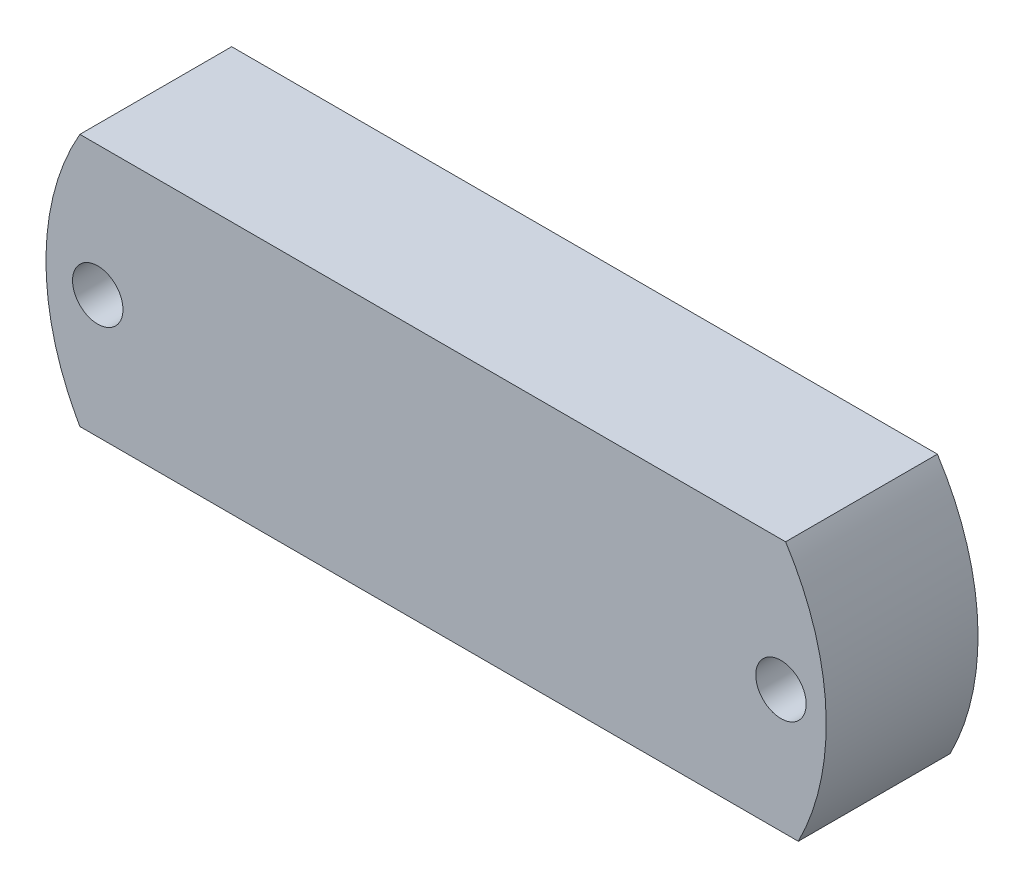
SolidWorks part; units mm, degrees
material "ABS PC"
ref_plane "Front Plane" through (0, 0, 0) normal (0, 0, 1) x (1, 0, 0)
ref_plane "Top Plane" through (0, 0, 0) normal (0, 1, 0) x (1, 0, 0)
ref_plane "Right Plane" through (0, 0, 0) normal (1, 0, 0) x (0, 0, -1)
sketch "Sketch1" plane through (0, 0, 0) normal (0, 0, 1) x (1, 0, 0)
  circle A0 centre (0, 0) radius 66.4845
  dimension "D1" = 132.969
extrude "Boss-Extrude1" add sketch "Sketch1" along normal blind 11.43
sketch "Sketch2" plane through (0, 0, 0) normal (0, 0, -1) x (-1, 0, 0)
  line L0 (0, 66.4845) -> (85.1652, 66.4845) construction
  circle A0 centre (0, 0) radius 66.4845 construction
ref_plane "Plane1" through (0, 10.9988, -24.7038) normal (0, -0.4067, 0.9135) x (1, 0, 0)
sketch "Sketch3" plane through (0, 10.9988, -24.7038) normal (0, -0.4067, 0.9135) x (1, 0, 0)
  line L1 (27.5387, 25.5449) -> (-13.7363, 25.5449)
  line L2 (27.5387, 25.5449) -> (27.5387, 49.8019)
  line L3 (27.5387, 49.8019) -> (-13.7363, 49.8019)
  line L4 (-13.7363, 25.5449) -> (-13.7363, 49.8019)
  line L5 (27.5387, 25.5449) -> (-13.7363, 49.8019) construction
  line L6 (27.5387, 49.8019) -> (-13.7363, 25.5449) construction
  line L7 (0, 60.7366) -> (-85.1652, 60.7366) construction
  point P0 (6.9012, 37.6734)
  dimension "D1" = 41.275
  dimension "D2" = 13.7363
  dimension "D3" = 35.1917
  dimension "D4" = 24.257
extrude "Cut-Extrude1" cut sketch "Sketch3" against normal blind 33.02 and the other way blind 13.2589
sketch "Sketch4" plane through (0, 0, 0) normal (0, 0, -1) x (-1, 0, 0)
  circle A0 centre (0, 0) radius 30.1625
  dimension "D1" = 60.325
extrude "Cut-Extrude2" cut sketch "Sketch4" against normal through all
sketch "Sketch6" plane through (0, 0, 0) normal (0, 0, -1) x (-1, 0, 0)
  line L0 (-32.6187, 45.625) -> (18.8163, 45.625) construction
  line L1 (-27.5387, 33.8863) -> (-27.5387, 51.1023) construction
  line L2 (13.7363, 33.8863) -> (13.7363, 54.515) construction
  line L3 (13.7363, 54.515) -> (-27.5387, 54.515) construction
  dimension "D1" = 5.08
  dimension "D2" = 5.08
  dimension "D3" = 8.89
hole_wizard "#6 Clearance Hole1" positions "Sketch8" profile "Sketch7" hole size "#6" standard "ANSI Inch" end condition through all
sketch "Sketch8" plane through (0, 0, 0) normal (0, 0, -1) x (-1, 0, 0)
  point P0 (-32.6187, 45.625)
  point P3 (18.8163, 45.625)
sketch "Sketch7" plane through (32.6187, 45.625, 0) normal (1, 0, 0) x (0, 1, 0)
  line L0 (0, 0) -> (0, 11.43)
  line L1 (0, 11.43) -> (1.8986, 11.43)
  line L2 (1.8986, 11.43) -> (1.8986, 0)
  line L5 (1.8986, 0) -> (0, 0)
  line L11 (0, -6.35) -> (0, 107.95) construction
  dimension "Thru Hole Dia." = 3.7973
  dimension "Thru Hole Depth" = 11.43
pattern_circular "CirPattern1" count 5 over 360 about axis through (0, 0, 0) along (0, 0, 1) of "Cut-Extrude1", "#6 Clearance Hole1"
sketch "Sketch5" plane through (0, 0, 0) normal (0, 0, -1) x (-1, 0, 0)
  line L0 (-45.3423, 48.6237) -> (0, 0)
  line L1 (0, 0) -> (32.2323, 58.1487)
  line L2 (0, 66.4845) -> (0, 0) construction
  arc A0 (32.2323, 58.1487) -> (-45.3423, 48.6237) centre (0, 0) cw
  circle A1 centre (0, 0) radius 66.4845 construction
  dimension "D1" = 72
  dimension "D2" = 29
extrude "Cut-Extrude3" cut sketch "Sketch5" against normal through all
sketch "Sketch9" plane through (0, 0, 11.43) normal (0, 0, 1) x (1, 0, 0)
  line L0 (-20.1644, 36.3776) -> (33.9227, 36.3776)
  line L1 (-32.2323, 58.1487) -> (-14.6231, 26.3807) construction
  line L2 (33.9227, 36.3776) -> (0, 0)
  line L3 (-20.1644, 36.3776) -> (0, 0)
  line L4 (32.6187, 45.625) -> (-18.8163, 45.625) construction
  line L5 (20.5708, 22.0595) -> (45.3423, 48.6237) construction
  line L6 (-35.9793, 55.4276) -> (54.1902, 55.4276)
  line L7 (-35.9793, 55.4276) -> (-35.9793, 74.5624)
  line L8 (-35.9793, 74.5624) -> (54.1902, 74.5624)
  line L9 (54.1902, 74.5624) -> (54.1902, 55.4276)
  dimension "D1" = 19.05
  dimension "D2" = 11.43
extrude "Cut-Extrude4" cut sketch "Sketch9" against normal through all
sketch "Sketch10" plane through (0, 0, 11.43) normal (0, 0, 1) x (1, 0, 0)
  line L0 (-30.724, 55.4276) -> (36.7147, 55.4276) construction
  line L1 (-20.1644, 36.3776) -> (-37.3283, 36.3776)
  line L2 (-37.3283, 36.3776) -> (-35.7165, 61.3072)
  line L3 (-35.7165, 61.3072) -> (-20.1644, 55.4276)
  line L4 (33.9227, 36.3776) -> (47.3752, 33.1988)
  line L5 (47.3752, 33.1988) -> (54.1577, 61.902)
  line L6 (54.1577, 61.902) -> (32.966, 55.4276)
  arc A0 (-20.1644, 36.3776) -> (-20.1644, 55.4276) centre (-3.6667, 45.9026) cw
  arc A1 (33.9227, 36.3776) -> (32.966, 55.4276) centre (16.9742, 45.0755) ccw
  dimension "D1" = 19.05
extrude "Cut-Extrude5" cut sketch "Sketch10" against normal through all
